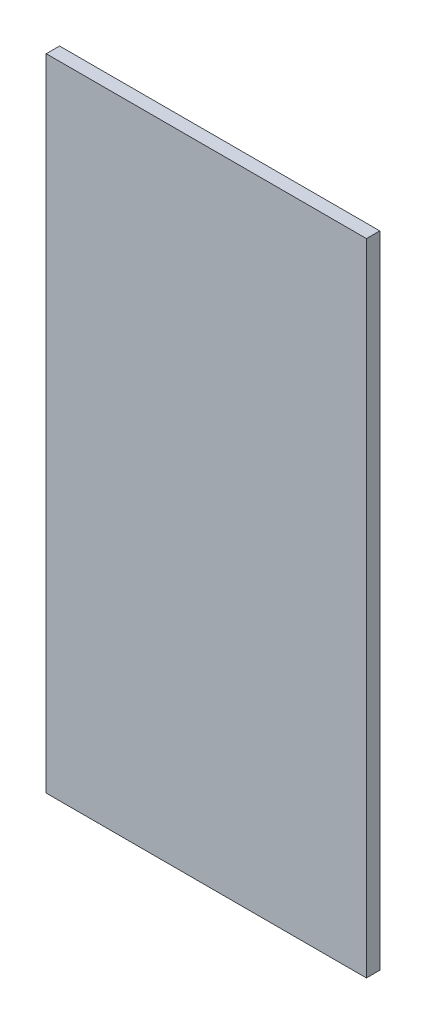
SolidWorks part; units mm, degrees
ref_plane "Front Plane" through (0, 0, 0) normal (0, 0, 1) x (1, 0, 0)
ref_plane "Top Plane" through (0, 0, 0) normal (0, 1, 0) x (1, 0, 0)
ref_plane "Right Plane" through (0, 0, 0) normal (1, 0, 0) x (0, 0, -1)
sketch "Sketch1" plane through (0, 0, 0) normal (0, 0, 1) x (1, 0, 0)
  line L1 (0, 0) -> (1219.2, 0)
  line L2 (0, 0) -> (0, 2438.4)
  line L3 (0, 2438.4) -> (1219.2, 2438.4)
  line L4 (1219.2, 0) -> (1219.2, 2438.4)
  dimension "D1" = 2438.4
  dimension "D2" = 1219.2
extrude "Boss-Extrude1" add sketch "Sketch1" against normal blind 50.8
